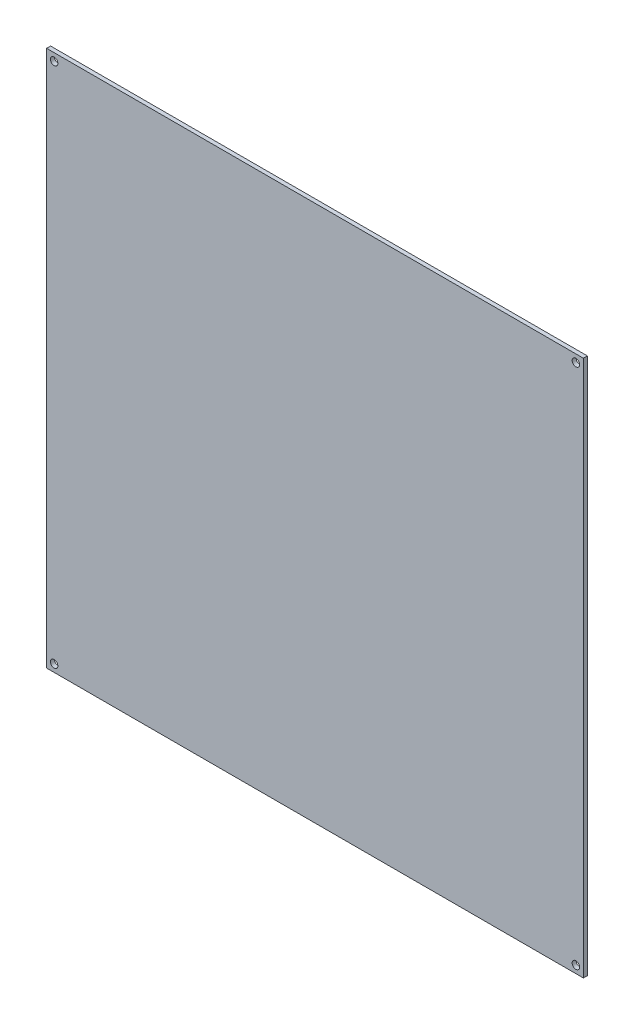
SolidWorks part; units mm, degrees
ref_plane "Front" through (0, 0, 0) normal (0, 0, 1) x (1, 0, 0)
ref_plane "Top" through (0, 0, 0) normal (0, 1, 0) x (1, 0, 0)
ref_plane "Right" through (0, 0, 0) normal (1, 0, 0) x (0, 0, -1)
sketch "Sketch1" plane through (0, 0, 0) normal (0, 0, 1) x (1, 0, 0)
  line L1 (-107.5, -107.5) -> (107.5, -107.5)
  line L2 (-107.5, -107.5) -> (-107.5, 107.5)
  line L3 (-107.5, 107.5) -> (107.5, 107.5)
  line L4 (107.5, -107.5) -> (107.5, 107.5)
  line L5 (-107.5, -107.5) -> (107.5, 107.5) construction
  line L6 (-107.5, 107.5) -> (107.5, -107.5) construction
  point P0 (0, 0)
  dimension "D1" = 215
  dimension "D2" = 215
extrude "Boss-Extrude1" add sketch "Sketch1" along normal blind 1.6
sketch "Sketch2" plane through (0, 0, 1.6) normal (0, 0, 1) x (1, 0, 0)
  line L1 (-104.5, -104.5) -> (104.5, -104.5) construction
  line L2 (-104.5, -104.5) -> (-104.5, 104.5) construction
  line L3 (-104.5, 104.5) -> (104.5, 104.5) construction
  line L4 (104.5, -104.5) -> (104.5, 104.5) construction
  line L5 (-104.5, -104.5) -> (104.5, 104.5) construction
  line L6 (-104.5, 104.5) -> (104.5, -104.5) construction
  circle A0 centre (-104.5, 104.5) radius 1.5
  circle A1 centre (104.5, 104.5) radius 1.5
  circle A2 centre (104.5, -104.5) radius 1.5
  circle A3 centre (-104.5, -104.5) radius 1.5
  point P0 (0, 0)
  dimension "D2" = 3
  dimension "D1" = 209
extrude "Cut-Extrude1" cut sketch "Sketch2" against normal through all
